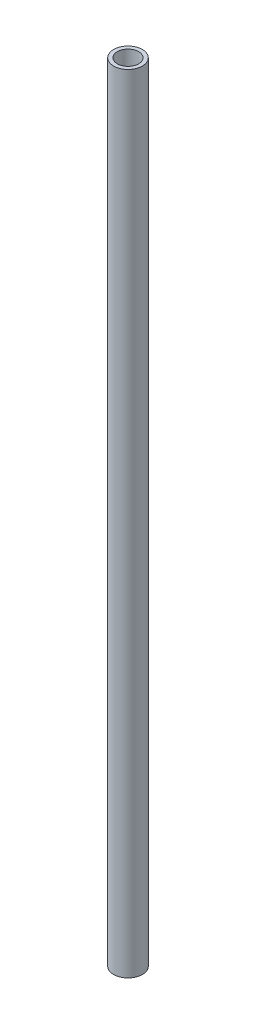
SolidWorks part; units mm, degrees
material "6061 Alloy"
ref_plane "Front Plane" through (0, 0, 0) normal (0, 0, 1) x (1, 0, 0)
ref_plane "Top Plane" through (0, 0, 0) normal (0, 1, 0) x (1, 0, 0)
ref_plane "Right Plane" through (0, 0, 0) normal (1, 0, 0) x (0, 0, -1)
sketch "Sketch1" plane through (0, 0, 0) normal (0, 1, 0) x (1, 0, 0)
  circle A0 centre (0, 0) radius 6.35
  circle A1 centre (0, 0) radius 4.699
  dimension "D1" = 12.7
  dimension "D2" = 1.651
extrude "Boss-Extrude1" add sketch "Sketch1" along normal blind 347.98
